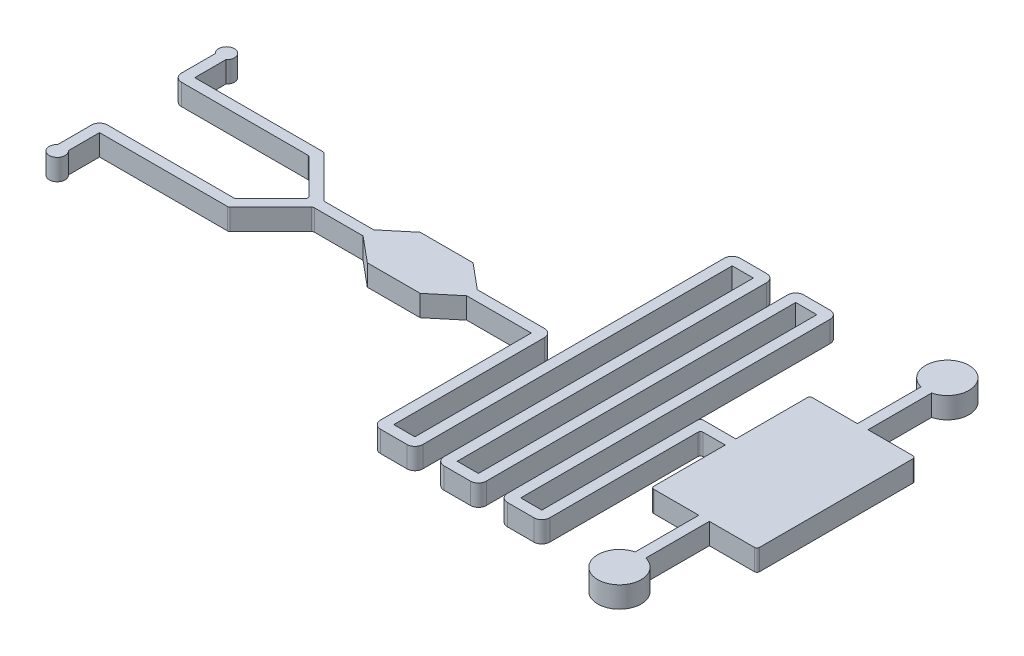
SolidWorks part; units mm, degrees
ref_plane "Front Plane" through (0, 0, 0) normal (0, 0, 1) x (1, 0, 0)
ref_plane "Top Plane" through (0, 0, 0) normal (0, 1, 0) x (1, 0, 0)
ref_plane "Right Plane" through (0, 0, 0) normal (1, 0, 0) x (0, 0, -1)
sketch "Sketch2" plane through (0, 0, 0) normal (0, 1, 0) x (1, 0, 0)
  line L0 (0, 0) -> (1.8251, 0) construction
  line L1 (15.1638, 7.25) -> (15.1638, -7.25)
  line L2 (14.9138, 7.5) -> (10.6638, 7.5)
  line L3 (14.9138, -7.5) -> (10.6638, -7.5)
  line L4 (5.1638, 7.25) -> (5.1638, 0.5)
  line L5 (5.1638, -0.5) -> (5.1638, -7.25)
  line L6 (9.6638, 7.5) -> (5.4138, 7.5)
  line L8 (5.1638, 0) -> (15.1638, 0) construction
  line L9 (9.6638, -7.5) -> (5.4138, -7.5)
  line L13 (9.6638, -7.5) -> (9.6638, -15.5) construction
  line L14 (10.1638, -7.5) -> (10.1638, -15.5) construction
  line L15 (10.6638, -7.5) -> (10.6638, -15.5) construction
  line L16 (9.6638, 7.5) -> (9.6638, 15.5) construction
  line L17 (10.1638, 7.5) -> (10.1638, 15.5) construction
  line L19 (-21.6749, 2.5) -> (-26.6749, 2.5)
  line L20 (-21.6749, -2.5) -> (-26.6749, -2.5)
  line L22 (10.6638, 7.5) -> (10.6638, 15.5) construction
  line L24 (-26.6749, 2.5) -> (-29.0749, 0.5)
  line L25 (-29.0749, -0.5) -> (-26.6749, -2.5)
  line L26 (-19.2749, -0.5) -> (-21.6749, -2.5)
  line L27 (-21.6749, 2.5) -> (-19.2749, 0.5)
  line L28 (-33.8585, 0.5732) -> (-37.7121, 4.4268)
  line L39 (10.1638, 13.45) -> (10.1638, 15.5) construction
  line L40 (10.1638, -7.5) -> (10.1638, -13.45) construction
  line L41 (-0.1749, -14.5) -> (-0.1749, 14.75)
  line L42 (5.1638, 0.5) -> (2.0751, 0.5)
  line L43 (1.8251, 0.25) -> (1.8251, -14.5)
  line L44 (1.8251, -14.5) -> (-0.1749, -14.5)
  line L45 (-1.1749, -14.75) -> (-1.1749, 14.5)
  line L46 (5.1638, -0.5) -> (3.0751, -0.5)
  line L47 (2.8251, -0.75) -> (2.8251, -14.75)
  line L48 (2.0751, -15.5) -> (-0.4249, -15.5)
  line L49 (-0.9249, 15.5) -> (-3.4249, 15.5)
  line L50 (-4.1749, 14.75) -> (-4.1749, -14.5)
  line L51 (-4.1749, -14.5) -> (-6.1749, -14.5)
  line L52 (-6.1749, -14.5) -> (-6.1749, 14.75)
  line L53 (-6.9249, 15.5) -> (-9.4249, 15.5)
  line L54 (-10.1749, 14.75) -> (-10.1749, -14.5)
  line L55 (-10.1749, -14.5) -> (-12.1749, -14.5)
  line L57 (-19.2749, -0.5) -> (-13.1749, -0.5)
  line L58 (-1.1749, 14.5) -> (-3.1749, 14.5)
  line L59 (-3.1749, 14.5) -> (-3.1749, -14.75)
  line L60 (-3.9249, -15.5) -> (-6.4249, -15.5)
  line L61 (-7.1749, -14.75) -> (-7.1749, 14.5)
  line L62 (-7.1749, 14.5) -> (-9.1749, 14.5)
  line L63 (-9.1749, 14.5) -> (-9.1749, -14.75)
  line L64 (-9.9249, -15.5) -> (-12.4249, -15.5)
  line L65 (-13.1749, -14.75) -> (-13.1749, -0.5)
  line L66 (-19.2749, 0.5) -> (-12.9249, 0.5)
  line L67 (-37.8889, 4.5) -> (-46.9924, 4.5)
  line L68 (-29.0749, 0.5) -> (-33.6818, 0.5)
  line L69 (-34.8763, -0.1768) -> (-38.1263, -3.4268)
  line L70 (-38.3031, -3.5) -> (-50.2424, -3.5)
  line L71 (-49.9924, -4.5) -> (-49.9924, -7.441)
  line L72 (-49.9924, -4.5) -> (-46.9924, -4.5)
  line L75 (-50.9924, 4.25) -> (-50.9924, 7.441)
  line L76 (-50.2424, 3.5) -> (-46.2424, 3.5)
  line L77 (9.6638, -7.5) -> (9.6638, -13.5119)
  line L78 (10.6638, 7.5) -> (10.6638, 13.5119)
  line L79 (-34.8763, 0.1768) -> (-38.1263, 3.4268)
  line L80 (-38.3031, 3.5) -> (-46.2424, 3.5)
  line L81 (-29.0749, -0.5) -> (-33.6818, -0.5)
  line L82 (-33.8585, -0.5732) -> (-37.7121, -4.4268)
  line L83 (-37.8889, -4.5) -> (-46.9924, -4.5)
  line L84 (-50.9924, -4.25) -> (-50.9924, -7.441)
  line L88 (-49.9924, 4.5) -> (-49.9924, 7.441)
  line L89 (-49.9924, 4.5) -> (-46.9924, 4.5)
  line L90 (10.6638, -7.5) -> (10.6638, -13.5119)
  line L91 (9.6638, 7.5) -> (9.6638, 13.5119)
  line L108 (-12.1749, -14.5) -> (-12.1749, -0.25)
  arc A0 (15.1638, 7.25) -> (14.9138, 7.5) centre (14.9138, 7.25) ccw
  arc A1 (5.4138, 7.5) -> (5.1638, 7.25) centre (5.4138, 7.25) ccw
  arc A2 (14.9138, -7.5) -> (15.1638, -7.25) centre (14.9138, -7.25) ccw
  arc A3 (5.4138, -7.5) -> (5.1638, -7.25) centre (5.4138, -7.25) cw
  arc A4 (10.6638, 13.5119) -> (9.6638, 13.5119) centre (10.1638, 15.5) ccw
  arc A5 (-12.9249, 0.5) -> (-12.1749, -0.25) centre (-12.9249, -0.25) cw
  arc A6 (9.6638, -13.5119) -> (10.6638, -13.5119) centre (10.1638, -15.5) ccw
  arc A7 (-50.9924, -7.441) -> (-49.9924, -7.441) centre (-50.4924, -8) ccw
  arc A10 (-49.9924, 7.441) -> (-50.9924, 7.441) centre (-50.4924, 8) ccw
  arc A11 (1.8251, 0.25) -> (2.0751, 0.5) centre (2.0751, 0.25) cw
  arc A12 (2.8251, -0.75) -> (3.0751, -0.5) centre (3.0751, -0.75) cw
  arc A15 (-37.8889, -4.5) -> (-37.7121, -4.4268) centre (-37.8889, -4.25) ccw
  arc A16 (-38.1263, -3.4268) -> (-38.3031, -3.5) centre (-38.3031, -3.25) cw
  arc A17 (-37.7121, 4.4268) -> (-37.8889, 4.5) centre (-37.8889, 4.25) ccw
  arc A18 (-38.1263, 3.4268) -> (-38.3031, 3.5) centre (-38.3031, 3.25) ccw
  arc A19 (-0.9249, 15.5) -> (-0.1749, 14.75) centre (-0.9249, 14.75) cw
  arc A20 (-3.4249, 15.5) -> (-4.1749, 14.75) centre (-3.4249, 14.75) ccw
  arc A21 (-33.8585, -0.5732) -> (-33.6818, -0.5) centre (-33.6818, -0.75) cw
  arc A22 (-33.6818, 0.5) -> (-33.8585, 0.5732) centre (-33.6818, 0.75) cw
  arc A23 (-6.9249, 15.5) -> (-6.1749, 14.75) centre (-6.9249, 14.75) cw
  arc A24 (-10.1749, 14.75) -> (-9.4249, 15.5) centre (-9.4249, 14.75) cw
  arc A25 (-34.8763, 0.1768) -> (-34.8763, -0.1768) centre (-35.0531, 0) cw
  arc A28 (2.0751, -15.5) -> (2.8251, -14.75) centre (2.0751, -14.75) ccw
  arc A31 (-3.1749, -14.75) -> (-3.9249, -15.5) centre (-3.9249, -14.75) cw
  arc A32 (-6.4249, -15.5) -> (-7.1749, -14.75) centre (-6.4249, -14.75) cw
  arc A35 (-9.1749, -14.75) -> (-9.9249, -15.5) centre (-9.9249, -14.75) cw
  arc A36 (-12.4249, -15.5) -> (-13.1749, -14.75) centre (-12.4249, -14.75) cw
  arc A37 (-0.4249, -15.5) -> (-1.1749, -14.75) centre (-0.4249, -14.75) cw
  arc A40 (-50.2424, 3.5) -> (-50.9924, 4.25) centre (-50.2424, 4.25) cw
  arc A41 (-50.2424, -3.5) -> (-50.9924, -4.25) centre (-50.2424, -4.25) ccw
  point P6 (15.1638, 0)
  point P14 (2.3251, 0)
  point P46 (15.1638, 7.5)
  point P51 (15.1638, -7.5)
  point P56 (-50.4924, -4)
  point P65 (-50.4924, 4)
  point P70 (-9.6749, 15)
  point P73 (-6.6749, 15)
  point P76 (-3.6749, 15)
  point P79 (-0.6749, 15)
  point P82 (-0.6749, -15)
  point P85 (-6.6749, -15)
  point P88 (-12.6749, -15)
  point P91 (-9.6749, -15)
  point P94 (-3.6749, -15)
  point P97 (2.3251, -15)
  dimension "D17" = 0.25
  dimension "D7" = 4.1
  dimension "D11" = 4.1
  dimension "D13" = 1.5
  dimension "D14" = 1.5
  dimension "D18" = 0.25
  dimension "D1" = 15
  dimension "D2" = 3
  dimension "D3" = 3
  dimension "D4" = 3
  dimension "D5" = 3
  dimension "D6" = 3
  dimension "D8" = 5
  dimension "D9" = 5
  dimension "D10" = 5
  dimension "D16" = 8
  dimension "D22" = 0.5
  dimension "D23" = 0.5
extrude "Boss-Extrude1" add sketch "Sketch2" along normal blind 2
